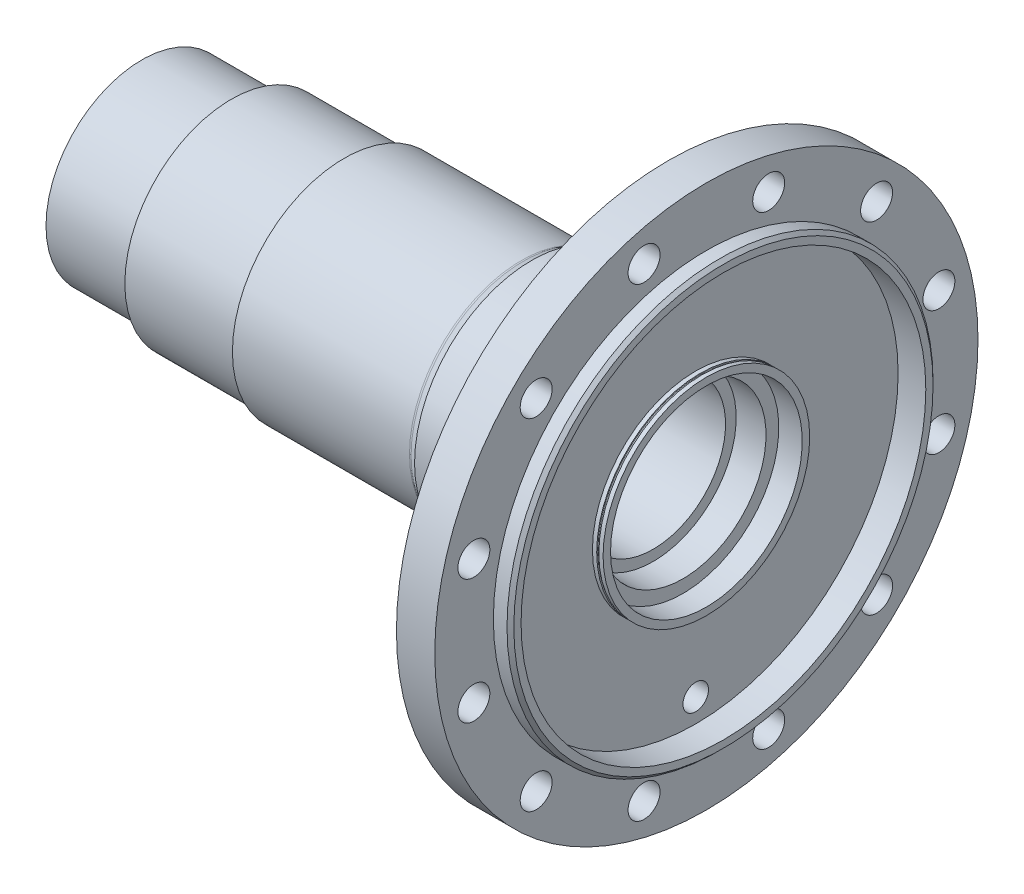
SolidWorks part; units mm, degrees
ref_plane "Спереди" through (0, 0, 0) normal (0, 0, 1) x (1, 0, 0)
ref_plane "Сверху" through (0, 0, 0) normal (0, 1, 0) x (1, 0, 0)
ref_plane "Справа" through (0, 0, 0) normal (1, 0, 0) x (0, 0, -1)
sketch "Эскиз1" plane through (0, 0, 0) normal (0, 0, 1) x (1, 0, 0)
  line L0 (0, 0) -> (273, 0)
  line L1 (0, 0) -> (0, 45)
  line L2 (0, 45) -> (42, 45)
  line L3 (42, 45) -> (42, 50)
  line L4 (42, 50) -> (95, 50)
  line L5 (95, 50) -> (95, 52.5)
  line L6 (95, 52.5) -> (178.134, 52.5)
  line L7 (179.134, 52.7679) -> (183, 55)
  line L8 (183, 55) -> (213, 55)
  line L9 (215, 57) -> (215, 60.7679)
  line L10 (215, 60.7679) -> (218, 62.5)
  line L11 (218, 62.5) -> (237, 62.5)
  line L12 (239, 64.5) -> (239, 65.5)
  line L13 (239, 65.5) -> (240.4142, 66.9142)
  line L14 (241, 68.3284) -> (241, 100)
  line L15 (241, 100) -> (247, 100)
  line L16 (247, 100) -> (247, 127.5)
  line L17 (247, 127.5) -> (265, 127.5)
  line L18 (265, 127.5) -> (265, 100)
  line L19 (265, 100) -> (271.4, 100)
  line L20 (271.4, 100) -> (273, 98.4)
  line L21 (273, 98.4) -> (273, 0)
  arc A0 (178.134, 52.5) -> (179.134, 52.7679) centre (178.134, 54.5) ccw
  arc A1 (213, 55) -> (215, 57) centre (213, 57) ccw
  arc A2 (237, 62.5) -> (239, 64.5) centre (237, 64.5) ccw
  arc A3 (240.4142, 66.9142) -> (241, 68.3284) centre (239, 68.3284) ccw
revolve "Повернуть1" add sketch "Эскиз1" angle 360 about L0
sketch "Эскиз2" plane through (0, 0, 0) normal (0, 0, 1) x (1, 0, 0)
  line L0 (0, 0) -> (273, 0)
  line L1 (0, 0) -> (0, 31)
  line L2 (0, 31) -> (203.5, 31)
  line L3 (203.5, 31) -> (203.5, 34)
  line L4 (203.5, 34) -> (240, 34)
  line L5 (240, 34) -> (240, 39)
  line L6 (240, 39) -> (254, 39)
  line L7 (254, 39) -> (254, 45)
  line L8 (254, 45) -> (265, 45)
  line L9 (265, 45) -> (265, 95)
  line L10 (265, 95) -> (273, 95)
  line L11 (273, 95) -> (273, 0)
revolve "Вырез-Повернуть1" cut sketch "Эскиз2" angle 360 about L0
sketch "Эскиз3" plane through (0, 0, 0) normal (0, 0, 1) x (1, 0, 0)
  line L0 (0, 0) -> (273, 0) construction
  line L1 (260, 48.5) -> (262, 48.5)
  line L2 (262, 48.5) -> (262, 95)
  line L3 (262, 95) -> (260, 95)
  line L4 (260, 95) -> (260, 48.5)
revolve "Rear_recess_left" cut sketch "Эскиз3" angle 360 about L0
sketch "Эскиз4" plane through (0, 0, 0) normal (0, 0, 1) x (1, 0, 0)
  line L0 (0, 0) -> (273, 0) construction
  line L1 (263, 48) -> (263, 95)
  line L2 (263, 95) -> (262, 95)
  line L3 (262, 95) -> (262, 48)
  arc A0 (262, 48) -> (262.5, 47.5) centre (262.5, 48) ccw
  arc A1 (262.5, 47.5) -> (263, 48) centre (262.5, 48) ccw
revolve "Collar_groove_nominal" cut sketch "Эскиз4" angle 360 about L0
sketch "Эскиз5" plane through (0, 0, 0) normal (0, 0, 1) x (1, 0, 0)
  line L0 (0, 0) -> (273, 0) construction
  line L1 (263, 48.5) -> (265, 48.5)
  line L2 (265, 48.5) -> (265, 95)
  line L3 (265, 95) -> (263, 95)
  line L4 (263, 95) -> (263, 48.5)
revolve "Rear_recess_lip" cut sketch "Эскиз5" angle 360 about L0
sketch "Эскиз6" plane through (0, 0, 0) normal (1, 0, 0) x (0, 0, -1)
  circle A0 centre (109.1496, 29.2466) radius 7.5
extrude "Вырез-Вытянуть1" cut sketch "Эскиз6" along normal through all
sketch "Эскиз7" plane through (0, 0, 0) normal (1, 0, 0) x (0, 0, -1)
  circle A0 centre (79.9031, 79.9031) radius 7.5
extrude "Вырез-Вытянуть2" cut sketch "Эскиз7" along normal through all
sketch "Эскиз8" plane through (0, 0, 0) normal (1, 0, 0) x (0, 0, -1)
  circle A0 centre (29.2466, 109.1496) radius 7.5
extrude "Вырез-Вытянуть3" cut sketch "Эскиз8" along normal through all
sketch "Эскиз9" plane through (0, 0, 0) normal (1, 0, 0) x (0, 0, -1)
  circle A0 centre (-29.2466, 109.1496) radius 7.5
extrude "Вырез-Вытянуть4" cut sketch "Эскиз9" along normal through all
sketch "Эскиз10" plane through (0, 0, 0) normal (1, 0, 0) x (0, 0, -1)
  circle A0 centre (-79.9031, 79.9031) radius 7.5
extrude "Вырез-Вытянуть5" cut sketch "Эскиз10" along normal through all
sketch "Эскиз11" plane through (0, 0, 0) normal (1, 0, 0) x (0, 0, -1)
  circle A0 centre (-109.1496, 29.2466) radius 7.5
extrude "Вырез-Вытянуть6" cut sketch "Эскиз11" along normal through all
sketch "Эскиз12" plane through (0, 0, 0) normal (1, 0, 0) x (0, 0, -1)
  circle A0 centre (-109.1496, -29.2466) radius 7.5
extrude "Вырез-Вытянуть7" cut sketch "Эскиз12" along normal through all
sketch "Эскиз13" plane through (0, 0, 0) normal (1, 0, 0) x (0, 0, -1)
  circle A0 centre (-79.9031, -79.9031) radius 7.5
extrude "Вырез-Вытянуть8" cut sketch "Эскиз13" along normal through all
sketch "Эскиз14" plane through (0, 0, 0) normal (1, 0, 0) x (0, 0, -1)
  circle A0 centre (-29.2466, -109.1496) radius 7.5
extrude "Вырез-Вытянуть9" cut sketch "Эскиз14" along normal through all
sketch "Эскиз15" plane through (0, 0, 0) normal (1, 0, 0) x (0, 0, -1)
  circle A0 centre (29.2466, -109.1496) radius 7.5
extrude "Вырез-Вытянуть10" cut sketch "Эскиз15" along normal through all
sketch "Эскиз16" plane through (0, 0, 0) normal (1, 0, 0) x (0, 0, -1)
  circle A0 centre (79.9031, -79.9031) radius 7.5
extrude "Вырез-Вытянуть11" cut sketch "Эскиз16" along normal through all
sketch "Эскиз17" plane through (0, 0, 0) normal (1, 0, 0) x (0, 0, -1)
  circle A0 centre (109.1496, -29.2466) radius 7.5
extrude "Вырез-Вытянуть12" cut sketch "Эскиз17" along normal through all
sketch "Эскиз18" plane through (0, 0, 0) normal (1, 0, 0) x (0, 0, -1)
  circle A0 centre (0, -84) radius 6
extrude "Вырез-Вытянуть13" cut sketch "Эскиз18" along normal through all
